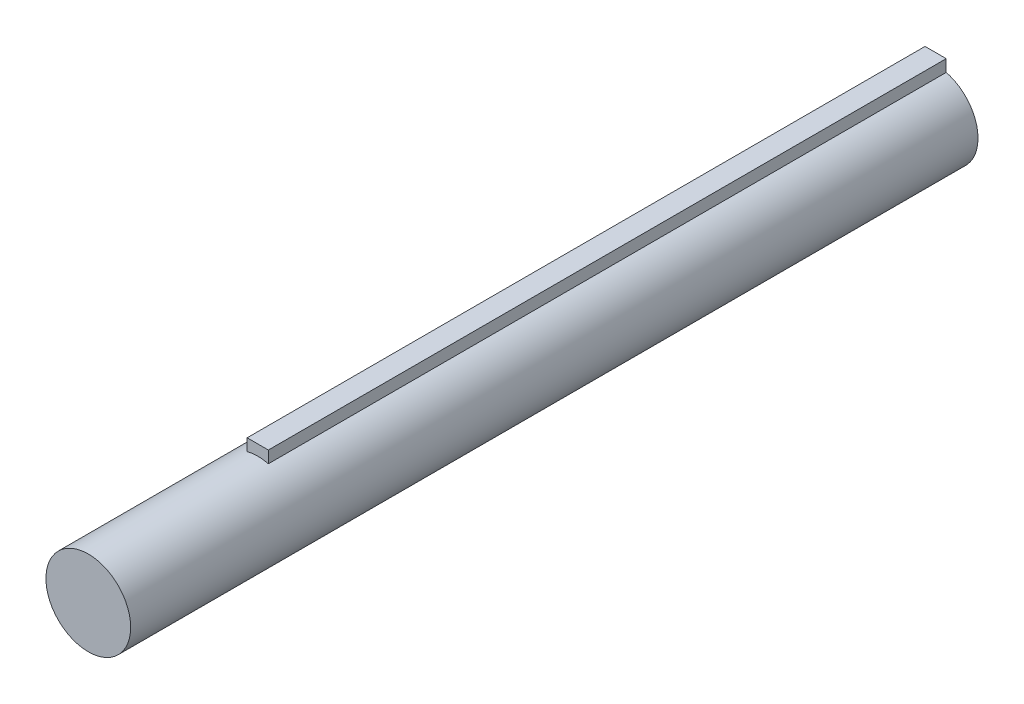
SolidWorks part; units mm, degrees
ref_plane "Front Plane" through (0, 0, 0) normal (0, 0, 1) x (1, 0, 0)
ref_plane "Top Plane" through (0, 0, 0) normal (0, 1, 0) x (1, 0, 0)
ref_plane "Right Plane" through (0, 0, 0) normal (1, 0, 0) x (0, 0, -1)
sketch "Sketch1" plane through (0, 0, 0) normal (0, 0, 1) x (1, 0, 0)
  circle A0 centre (0, 0) radius 10
  dimension "D1" = 20
extrude "Boss-Extrude1" add sketch "Sketch1" along normal blind 200
sketch "Sketch2" plane through (0, 0, 0) normal (0, 0, -1) x (-1, 0, 0)
  line L1 (-2.5, 12.5) -> (2.5, 12.5)
  line L2 (-2.5, 12.5) -> (-2.5, 9.6825)
  line L4 (2.5, 12.5) -> (2.5, 9.6825)
  line L5 (-2.5, 12.5) -> (-6.2564, 7.6703) construction
  line L6 (-6.2989, 7.8418) -> (2.5, 12.5) construction
  circle A0 centre (0, 0) radius 10 construction
  circle A1 centre (0, 0) radius 10 construction
  arc A2 (2.5, 9.6825) -> (-2.6052, 9.6547) centre (0, 0) ccw
  point P0 (-6, 8)
  point P13 (0, 12.5)
  circle M5 centre (0, 0) radius 10
  dimension "D1" = 5
  dimension "D2" = 10
  dimension "D3" = 12.5
extrude "Boss-Extrude2" add sketch "Sketch2" against normal blind 160 separate body contours L4 L1 L2 M5
